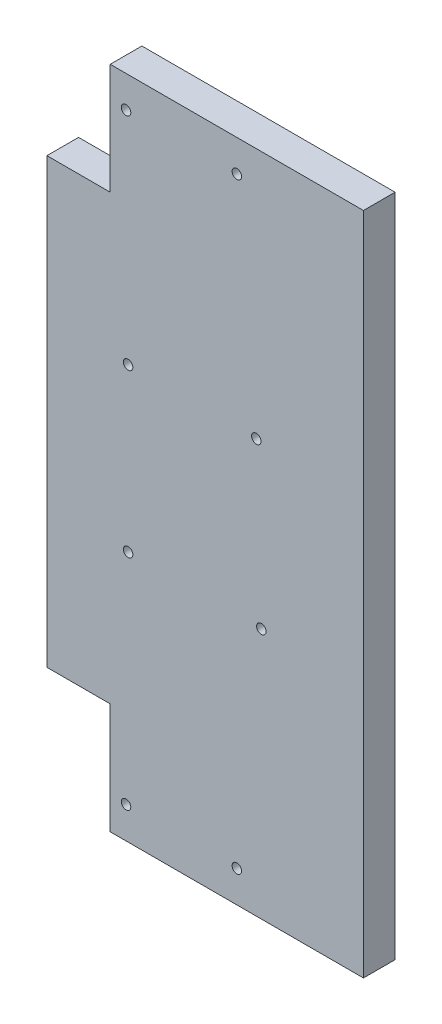
SolidWorks part; units mm, degrees
ref_plane "Plan de face" through (0, 0, 0) normal (0, 0, 1) x (1, 0, 0)
ref_plane "Plan de dessus" through (0, 0, 0) normal (0, 1, 0) x (1, 0, 0)
ref_plane "Plan de droite" through (0, 0, 0) normal (1, 0, 0) x (0, 0, -1)
sketch "Esquisse2" plane through (0, 0, 0) normal (0, 0, 1) x (1, 0, 0)
  line L1 (0, 0) -> (100, 0)
  line L2 (0, 0) -> (0, 210)
  line L3 (0, 210) -> (100, 210)
  line L4 (100, 0) -> (100, 210)
  point P5 (10, 4.8194)
  dimension "D1" = 100
  dimension "D2" = 210
extrude "Boss.-Extru.1" add sketch "Esquisse2" along normal blind 10
sketch "Esquisse3" plane through (0, 0, 0) normal (0, 0, 1) x (1, 0, 0)
  line L0 (0, 175) -> (20, 175)
  line L1 (0, 210) -> (0, 0) construction
  line L2 (20, 175) -> (20, 210)
  line L3 (100, 210) -> (0, 210) construction
  line L4 (0, 35) -> (20, 35)
  line L5 (20, 35) -> (20, 0)
  line L6 (0, 0) -> (100, 0) construction
  line L7 (20, 210) -> (0, 210)
  line L8 (0, 210) -> (0, 175)
  line L9 (0, 35) -> (0, 0)
  line L10 (0, 0) -> (20, 0)
  dimension "D1" = 140
  dimension "D2" = 35
  dimension "D3" = 20
  dimension "D4" = 20
extrude "Enlèv. mat.-Extru.1" cut sketch "Esquisse3" along normal blind 10
sketch "Esquisse4" plane through (0, 0, 0) normal (0, 0, -1) x (-1, 0, 0)
  line L0 (-20, 175) -> (-20, 210) construction
  line L3 (-20, 0) -> (-20, 35) construction
  line L4 (-100, 210) -> (-20, 210) construction
  line L5 (-20, 0) -> (-100, 0) construction
  circle A0 centre (-25, 200) radius 1.5
  circle A1 centre (-60, 200) radius 1.5
  circle A2 centre (-25, 10) radius 1.5
  circle A3 centre (-60, 10) radius 1.5
  point P12 (-78.9516, 7.8809)
  dimension "D1" = 3
  dimension "D2" = 3
  dimension "D3" = 3
  dimension "D4" = 3
  dimension "D5" = 35
  dimension "D6" = 35
  dimension "D7" = 5
  dimension "D8" = 5
  dimension "D10" = 10
  dimension "D11" = 10
  dimension "D12" = 10
  dimension "D9" = 10
extrude "Enlèv. mat.-Extru.2" cut sketch "Esquisse4" against normal blind 10
sketch "Esquisse6" plane through (0, 0, 0) normal (0, 0, -1) x (-1, 0, 0)
  circle A0 centre (-25.6459, 130.6337) radius 1.5
  circle A1 centre (-25.6459, 79.3859) radius 1.5
  circle A2 centre (-67.7423, 79.3859) radius 1.5
  circle A3 centre (-66.162, 130.6337) radius 1.5
  dimension "D1" = 3
  dimension "D2" = 3
  dimension "D3" = 3
  dimension "D4" = 3
extrude "Enlèv. mat.-Extru.3" cut sketch "Esquisse6" against normal blind 10
